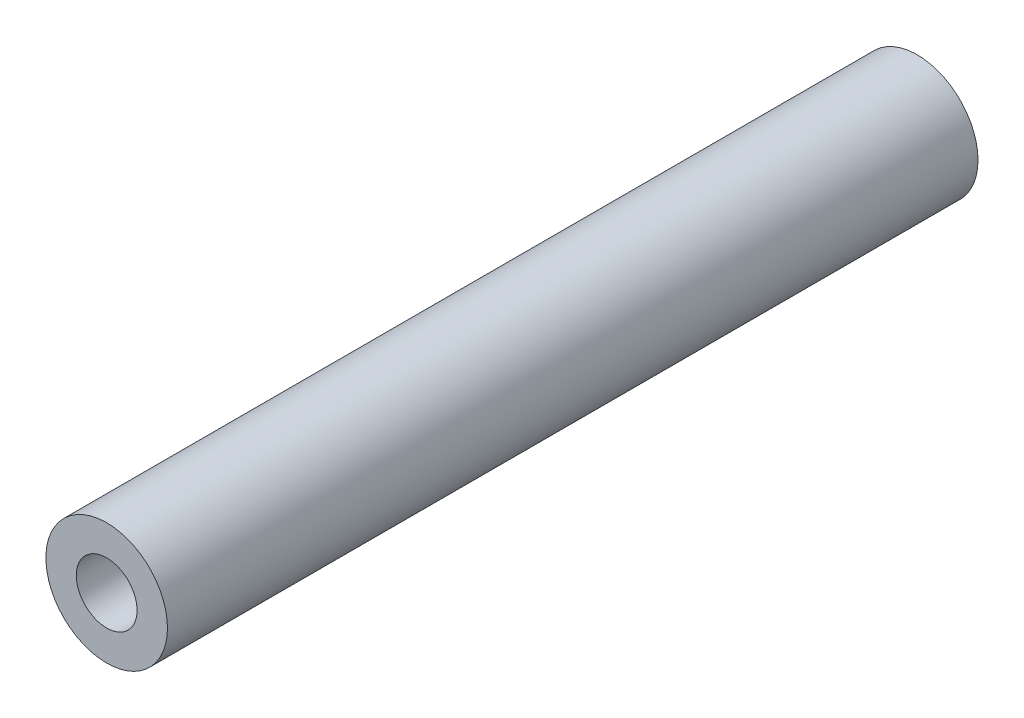
SolidWorks part; units mm, degrees
ref_plane "前视基准面" through (0, 0, 0) normal (0, 0, 1) x (1, 0, 0)
ref_plane "上视基准面" through (0, 0, 0) normal (0, 1, 0) x (1, 0, 0)
ref_plane "右视基准面" through (0, 0, 0) normal (1, 0, 0) x (0, 0, -1)
sketch "草图1" plane through (0, 0, 0) normal (0, 0, 1) x (1, 0, 0)
  circle A0 centre (0, 0) radius 3
  circle A1 centre (0, 0) radius 1.5
  dimension "D1" = 3
  dimension "D2" = 6
extrude "凸台-拉伸1" add sketch "草图1" along normal blind 40
